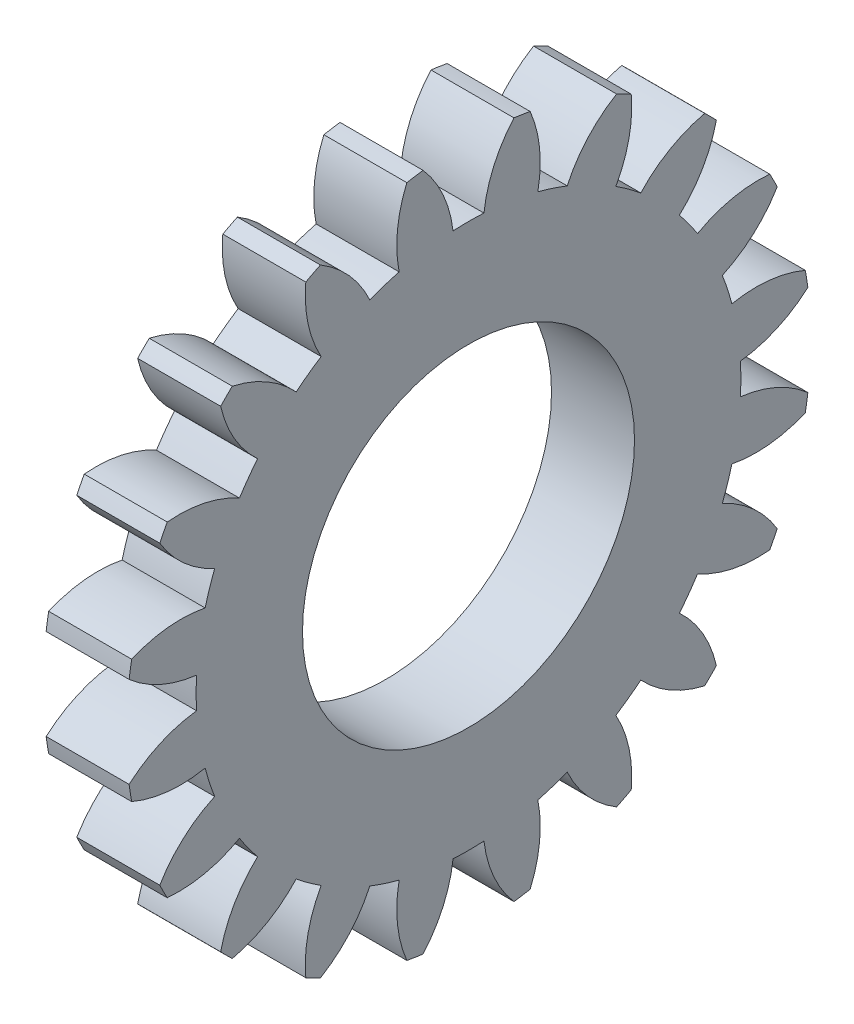
SolidWorks part; units mm, degrees
ref_plane "Plane1" through (0, 0, 0) normal (0, 0, 1) x (1, 0, 0)
ref_plane "Plane2" through (0, 0, 0) normal (0, 1, 0) x (1, 0, 0)
ref_plane "Plane3" through (0, 0, 0) normal (1, 0, 0) x (0, 0, -1)
other "Configuration Table"
sketch "HoldingSke" plane through (0, 0, 0) normal (0, 1, 0) x (1, 0, 0)
  line L0 (0, 0) -> (0.6265, -0.228)
  line L1 (-15, 0) -> (100, 0) construction
  line L2 (0, 0) -> (-2.1039, 2.3779)
  line L3 (0, 0) -> (-11.863, 4.5341)
  line L4 (0, 0) -> (8.1152, 2.9537)
  line L5 (0, 0) -> (-46.8476, -17.4728)
  line L6 (0, 0) -> (-3.3159, -2.2372)
  line L7 (-2.1039, 2.3779) -> (8.6586, 51.2059)
  line L8 (-76.2, 54.61) -> (-73.9, 54.61)
  line L9 (-71.009, 38.7566) -> (-53.1078, 45.2721)
  line L10 (-76.2, 71.12) -> (104.1128, 71.12)
  line L11 (0, 0) -> (-4, 0)
  line L12 (-76.2, 101.6) -> (-76.147, 101.6)
  line L13 (24.9733, 27.94) -> (52.9518, 28.4284)
  line L14 (24.9733, 27.94) -> (24.9743, 27.94)
  line L15 (24.9733, 27.94) -> (100.4006, 29.5858)
  line L16 (-63.627, -1.5) -> (-12.827, -1.5)
  circle A0 centre (0, 0) radius 8
  circle A1 centre (0, 0) radius 13.124
  circle A2 centre (0, 0) radius 37.5
  circle A3 centre (0, 0) radius 8
  dimension "MHD" = 26.248
  dimension "Hub_dia" = 75
  dimension "Bore" = 16
  dimension "MBD" = 16
  dimension "Num_teeth" = 20
  dimension "Pitch" = 0.6667
  dimension "Overall_len" = 50
  dimension "Show_teeth" = 20
  dimension "Thickness" = 4
  dimension "OAL" = 50.0001
  dimension "T_dim" = 2.3
  dimension "Ap" = 20
  dimension "H" = 19.05
  dimension "Pitch_radius" = 180.3128
  dimension "Width" = 4
  dimension "Backlash" = 0.053
  dimension "Addendum_fac" = 1
  dimension "Dedendum_fac" = 1.25
  dimension "Clearance_fac" = 0.25
  dimension "Dedendum_add" = 0.001
  dimension "Module" = 1.5
sketch "BasProSke" plane through (0, 0, 0) normal (0, 1, 0) x (1, 0, 0)
  line L0 (-10, 0) -> (60, 0) construction
  line L1 (0, 0) -> (0, 16.5)
  line L2 (0, 0) -> (4, 0)
  line L3 (4, 0) -> (4, 16.5)
  line L4 (4, 16.5) -> (0, 16.5)
  dimension "Thickness" = 4
  dimension "Diameter" = 33
revolve "Base-Revolve" add sketch "BasProSke" angle 360 about L0
sketch "TooCutSke" plane through (0, 0, 0) normal (1, 0, 0) x (0, 0, -1)
  line L1 (0, 0) -> (0, 107) construction
  line L2 (0, 0) -> (-1.2696, 14.9462) construction
  line L3 (0, 0) -> (-4.6808, 29.5532) construction
  line L4 (-1.2696, 14.9462) -> (-2.3404, 14.7766) construction
  arc A0 (0.7438, 13.1029) -> (-0.7438, 13.1029) centre (0, 0) ccw
  arc A1 (2.21, 16.377) -> (-2.21, 16.377) centre (0, 0) ccw
  circle A2 centre (0, 0) radius 15 construction
  circle A3 centre (0, 0) radius 14.0954 construction
  arc A4 (-0.7438, 13.1029) -> (-2.21, 16.377) centre (-6.7025, 12.3999) ccw
  arc A5 (2.21, 16.377) -> (0.7438, 13.1029) centre (6.7025, 12.3999) ccw
  dimension "Root_dia" = 26.248
  dimension "Overcut_dia" = 33.0508
  dimension "Pitch_dia" = 30
  dimension "Base_dia" = 28.1908
  dimension "Flank_rad" = 6
  dimension "Half_ang" = 9
  dimension "Half_CT" = 1.0841
extrude "ToothCut" cut sketch "TooCutSke" along normal through all
fillet "Breaks" [suppressed] radius 0.03
fillet "RootFillets" [suppressed] radius 0.376
pattern_circular "TeethCuts" count 20 every 18 about axis through (-10, 0, 0) along (1, 0, 0) of "ToothCut", "RootFillets", "Breaks"
sketch "HubNeaOneSke" plane through (0, 0, 0) normal (-1, 0, 0) x (0, 0, 1)
  circle A0 centre (0, 0) radius 13.124
  dimension "Diameter" = 26.248
extrude "HubNearOne" [suppressed] add sketch "HubNeaOneSke" along normal blind 46.0001
sketch "HubNeaBotSke" plane through (0, 0, 0) normal (-1, 0, 0) x (0, 0, 1)
  circle A0 centre (0, 0) radius 13.124
  dimension "Diameter" = 26.248
extrude "HubNearBoth" [suppressed] add sketch "HubNeaBotSke" along normal blind 23
ref_plane "FarPln" through (4, 0, 0) normal (1, 0, 0) x (0, 0, -1)
sketch "HubFarSke" plane through (4, 0, 0) normal (1, 0, 0) x (0, 0, -1)
  circle A0 centre (0, 0) radius 13.124
  dimension "Diameter" = 26.248
extrude "HubFar" [suppressed] add sketch "HubFarSke" along normal blind 23
sketch "BorSke" plane through (0, 0, 0) normal (1, 0, 0) x (0, 0, -1)
  circle A0 centre (0, 0) radius 8
  dimension "Diameter" = 16
extrude "Bore" cut sketch "BorSke" along normal mid plane 100.0001
sketch "KeySke" plane through (0, 0, 0) normal (1, 0, 0) x (0, 0, -1)
  line L0 (-2.5, 0) -> (-2.5, 10.3)
  line L1 (-2.5, 10.3) -> (2.5, 10.3)
  line L2 (2.5, 10.3) -> (2.5, 0)
  line L3 (0, 0) -> (0, 34) construction
  line L4 (-2.5, 0) -> (2.5, 0)
  dimension "Offset" = 10.3
  dimension "Width" = 5
extrude "Keyway" [suppressed] cut sketch "KeySke" along normal mid plane 100.0001
pattern_circular "Keyway2" [suppressed] count 2 every 90 about axis through (-10, 0, 0) along (1, 0, 0)
sketch "草图1" plane through (0, 0, 0) normal (-1, 0, 0) x (0, 0, 1)
  circle A0 centre (0, 0) radius 15
  dimension "D1" = 30
equation "' \"Module@HoldingSke\" = 6.35"
equation "' \"Num_teeth@HoldingSke\" = 12"
equation "' \"Ap@HoldingSke\" =  20"
equation "' \"Ap@HoldingSke\" = 20"
equation "' \"Width@HoldingSke\" = 0.5 * 25.4"
equation "' \"Hub_dia@HoldingSke\"= 1 * 25.4"
equation "' \"Hub_dia@HoldingSke\" = 1 * 25.4"
equation "' \"Overall_len@HoldingSke\" = 1.0 * 25.4"
equation "' \"Bore@HoldingSke\" = 0.75 * 25.4"
equation "' \"T_dim@HoldingSke\" = 0.1 * 25.4"
equation "' \"Width@KeySke\" = 0.25 * 25.4"
equation "' \"Show_teeth@HoldingSke\" = 13"
equation "' \"Backlash@HoldingSke\" = 0.009 * 25.4"
equation "' \"Addendum_fac@HoldingSke\" = 1.0"
equation "' \"Dedendum_fac@HoldingSke\" = 1.25"
equation "' \"Dedendum_add@HoldingSke\" = 0.00005 * 25.4"
equation "' \"Clearance_fac@HoldingSke\" = 0.25"
equation "\"Pitch@HoldingSke\" = 1 / \"Module@HoldingSke\""
equation "\"Overcut_dia@TooCutSke\" = (\"Num_teeth@HoldingSke\" + 2 * \"Addendum_fac@HoldingSke\") / \"Pitch@HoldingSke\" + 0.002 * 25.4"
equation "\"Pitch_dia@TooCutSke\" = \"Num_teeth@HoldingSke\" / \"Pitch@HoldingSke\""
equation "\"Base_dia@TooCutSke\" = \"Num_teeth@HoldingSke\" / \"Pitch@HoldingSke\" * cos((\"Ap@HoldingSke\"  * 3.14159265 / 180))"
equation "\"Root_dia@TooCutSke\" = (\"Num_teeth@HoldingSke\" + 2) / \"Pitch@HoldingSke\" - 2 * (\"Addendum_fac@HoldingSke\" + \"Dedendum_fac@HoldingSke\") / \"Pitch@HoldingSke\" - \"Dedendum_add@HoldingSke\" * 2"
equation "\"Half_ang@TooCutSke\" = 180 / \"Num_teeth@HoldingSke\""
equation "\"Half_CT@TooCutSke\" = \"Num_teeth@HoldingSke\" / \"Pitch@HoldingSke\" * sin((3.14159265 / 2 / \"Num_teeth@HoldingSke\")) / 2 - 7 * \"Backlash@HoldingSke\" / 4"
equation "\"Flank_rad@TooCutSke\" = \"Num_teeth@HoldingSke\" / \"Pitch@HoldingSke\" / 5"
equation "\"Radius@RootFillets\" = \"Clearance_fac@HoldingSke\" / \"Pitch@HoldingSke\" + \"Dedendum_add@HoldingSke\""
equation "\"Break_rad@Breaks\" = 0.02 / \"Pitch@HoldingSke\""
equation "\"Thickness@HoldingSke\" = \"Width@HoldingSke\""
equation "\"OAL@HoldingSke\" = \"Thickness@HoldingSke\""
equation "\"MHD@HoldingSke\" = (\"Num_teeth@HoldingSke\" + 2) / \"Pitch@HoldingSke\" - 2 * (\"Addendum_fac@HoldingSke\" + \"Dedendum_fac@HoldingSke\")  / \"Pitch@HoldingSke\" - \"Dedendum_add@HoldingSke\" * 2"
equation "\"MBD@HoldingSke\" = (\"Num_teeth@HoldingSke\" + 2) / \"Pitch@HoldingSke\" - 2 * (\"Addendum_fac@HoldingSke\" + \"Dedendum_fac@HoldingSke\")  / \"Pitch@HoldingSke\" - \"Dedendum_add@HoldingSke\" * 2 - 0.002 * 25.4"
equation "\"MHD@HoldingSke\" = ((sgn( \"MHD@HoldingSke\" - \"Hub_dia@HoldingSke\" )-1)*( \"MHD@HoldingSke\" - \"Hub_dia@HoldingSke\" ))/-2+ \"Hub_dia@HoldingSke\""
equation "\"MBD@HoldingSke\" = ((sgn( \"MBD@HoldingSke\" - \"Bore@HoldingSke\" )-1)*( \"MBD@HoldingSke\" - \"Bore@HoldingSke\" ))/-2+ \"Bore@HoldingSke\""
equation "\"OAL@HoldingSke\" = ((sgn( \"OAL@HoldingSke\" - \"Overall_len@HoldingSke\" )+1)*( \"OAL@HoldingSke\" - \"Overall_len@HoldingSke\" ))/2 + \"Overall_len@HoldingSke\" + 0.000002 * 25.4"
equation "\"Num_teeth@TeethCuts\" = int( \"Show_teeth@HoldingSke\" ) + 1"
equation "\"Num_teeth@TeethCuts\" = ((sgn( \"Num_teeth@TeethCuts\" - \"Num_teeth@HoldingSke\" )-1)*( \"Num_teeth@TeethCuts\" - \"Num_teeth@HoldingSke\" ))/-2+ \"Num_teeth@HoldingSke\""
equation "\"Num_teeth@TeethCuts\" = ((sgn( \"Num_teeth@TeethCuts\" - 2.0)+1)*( \"Num_teeth@TeethCuts\" - 2.0))/2 +2.0"
equation "\"Angle@TeethCuts\" = 360.0 / \"Num_teeth@HoldingSke\""
equation "\"Diameter@BasProSke\" = (\"Num_teeth@HoldingSke\" + 2 * \"Addendum_fac@HoldingSke\") / \"Pitch@HoldingSke\""
equation "\"Thickness@BasProSke\"  = \"Thickness@HoldingSke\""
equation "' \"Fillet_rad@BasProSke\" =  \"Thickness@HoldingSke\" * 0.05"
equation "' \"Fillet_rad@BasProSke\" = \"Thickness@HoldingSke\" * 0.05"
equation "\"MHD@HoldingSke\" = ((sgn( \"MHD@HoldingSke\" - \"Root_dia@TooCutSke\" )-1)*( \"MHD@HoldingSke\" - \"Root_dia@TooCutSke\" ))/-2+ \"Root_dia@TooCutSke\""
equation "\"Diameter@HubNeaOneSke\" = \"MHD@HoldingSke\""
equation "\"Length@HubNearOne\" = \"OAL@HoldingSke\" - \"Thickness@BasProSke\""
equation "\"Diameter@HubNeaBotSke\" = \"MHD@HoldingSke\""
equation "\"Length@HubNearBoth\" = ( \"OAL@HoldingSke\" - \"Thickness@BasProSke\" ) / 2.0"
equation "\"Thickness@FarPln\" = \"Thickness@BasProSke\""
equation "\"Diameter@HubFarSke\" = \"MHD@HoldingSke\""
equation "\"Length@HubFar\" = ( \"OAL@HoldingSke\" - \"Thickness@BasProSke\" ) / 2.0"
equation "\"Diameter@BorSke\" = \"MBD@HoldingSke\""
equation "\"D1@Bore\" = \"OAL@HoldingSke\" * 2.0"
equation "\"D1@Keyway\" = \"OAL@HoldingSke\" * 2.0"
equation "\"Offset@KeySke\" = \"T_dim@HoldingSke\" + \"MBD@HoldingSke\" / 2.0"
